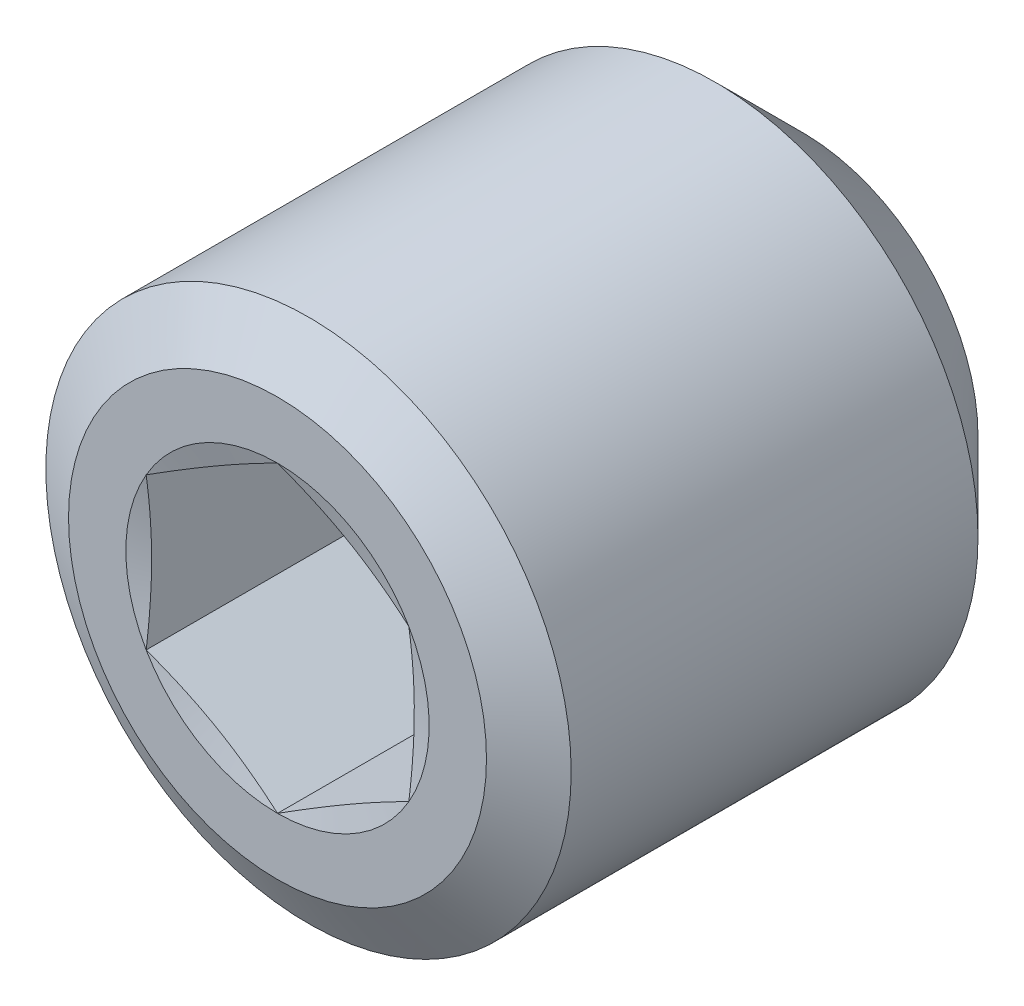
SolidWorks part; units mm, degrees
ref_plane "Front Plane" through (0, 0, 0) normal (0, 0, 1) x (1, 0, 0)
ref_plane "Top Plane" through (0, 0, 0) normal (0, 1, 0) x (1, 0, 0)
ref_plane "Right Plane" through (0, 0, 0) normal (1, 0, 0) x (0, 0, -1)
sketch "Sketch1" plane through (0, 0, 0) normal (1, 0, 0) x (0, 0, -1)
  line L0 (0, 0) -> (19.8153, 0) construction
  line L3 (0.1771, 1.5) -> (2.5, 1.5)
  line L4 (2.5, 1.5) -> (3, 1)
  line L5 (3, 1) -> (3, 0)
  line L8 (0, 0.75) -> (1.2, 0.75)
  line L9 (1.2, 0.75) -> (1.633, 0)
  line L10 (1.633, 0) -> (3, 0)
  line L12 (0, 0.75) -> (0, 1.1933)
  line L13 (0, 1.1933) -> (0.1771, 1.5)
  dimension "D1" = 60
  dimension "S1" = 1.5
  dimension "T1" = 1.2
  dimension "HoleSize" = 3
  dimension "D3" = 60
  dimension "D5" = 45
  dimension "Dp" = 2
  dimension "DF" = 2.3866
  dimension "Length" = 3
revolve "Revolve1" add sketch "Sketch1" angle 360 about L0
cosmetic thread "Cosmetic Thread1" parameters "D2"=3
sketch "Sketch2" plane through (0, 0, 0) normal (0, 0, 1) x (1, 0, 0)
  line L0 (0, 0) -> (0, 0.866) construction
  line L1 (0, 0.866) -> (-0.75, 0.433)
  line L2 (-0.75, 0.433) -> (-0.75, -0.433)
  line L3 (-0.75, -0.433) -> (0, -0.866)
  line L4 (0, -0.866) -> (0.75, -0.433)
  line L5 (0.75, -0.433) -> (0.75, 0.433)
  line L6 (0.75, 0.433) -> (0, 0.866)
  circle A0 centre (0, 0) radius 0.75 construction
  dimension "S2" = 1.5
extrude "Cut-Extrude1" cut sketch "Sketch2" against normal blind 1.2
sketch "Sketch3" plane through (0, 0, 0) normal (1, 0, 0) x (0, 0, -1)
  line L0 (0, 0.75) -> (0, 0.866)
  line L1 (0, 0.866) -> (0.0311, 0.75)
  line L2 (0.0311, 0.75) -> (0, 0.75)
  line L3 (0, 0) -> (2.1263, 0) construction
  dimension "D1" = 15
  dimension "S3" = 1.5
revolve "Cut-Revolve2" cut sketch "Sketch3" angle 360 about L3
